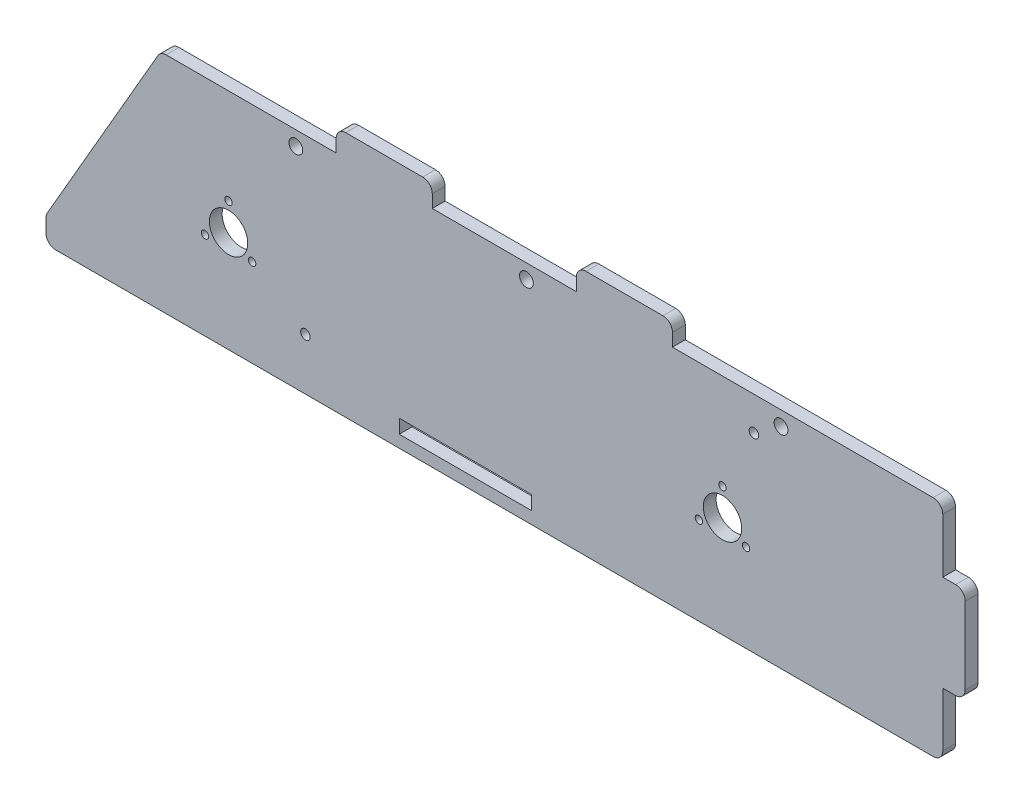
SolidWorks part; units mm, degrees
ref_plane "Front Plane" through (0, 0, 0) normal (0, 0, 1) x (1, 0, 0)
ref_plane "Top Plane" through (0, 0, 0) normal (0, 1, 0) x (1, 0, 0)
ref_plane "Right Plane" through (0, 0, 0) normal (1, 0, 0) x (0, 0, -1)
sketch "Sketch1" plane through (0, 0, 0) normal (0, 0, 1) x (1, 0, 0)
  line L0 (-128.1718, -30) -> (151.8282, -30)
  line L1 (-128.1718, -30) -> (-128.1718, -22)
  line L2 (-128.1718, -22) -> (-92.376, 40)
  line L5 (-37.566, 40) -> (-37.566, 47)
  line L6 (-37.566, 47) -> (-7.566, 47)
  line L7 (-7.566, 47) -> (-7.566, 40)
  line L8 (37.434, 40) -> (37.434, 47)
  line L9 (37.434, 47) -> (67.434, 47)
  line L10 (67.434, 47) -> (67.434, 40)
  line L11 (-92.376, 40) -> (-37.566, 40)
  line L12 (-7.566, 40) -> (37.434, 40)
  line L13 (67.434, 40) -> (151.8282, 40)
  line L16 (158.8282, 5) -> (158.8282, 20)
  line L17 (158.8282, 5) -> (158.8282, -10)
  line L18 (158.8282, -10) -> (151.8282, -10)
  line L19 (158.8282, 20) -> (151.8282, 20)
  line L20 (151.8282, 40) -> (151.8282, 20)
  line L21 (151.8282, -10) -> (151.8282, -30)
  line L22 (-17.8718, -21.85) -> (23.4282, -21.85)
  line L23 (-17.8718, -21.85) -> (-17.8718, -26.2)
  line L24 (-17.8718, -26.2) -> (23.4282, -26.2)
  line L25 (23.4282, -21.85) -> (23.4282, -26.2)
  circle A0 centre (-71.1757, 1.72) radius 6
  circle A3 centre (-71.1757, 1.72) radius 8.5 construction
  circle A4 centre (-71.1757, 10.22) radius 1.15
  circle A5 centre (-63.8145, -2.53) radius 1.15
  circle A6 centre (-78.537, -2.53) radius 1.15
  circle A7 centre (83.0482, 1.72) radius 6
  circle A8 centre (83.0482, 1.72) radius 8.5 construction
  circle A9 centre (83.0482, 10.22) radius 1.15
  circle A10 centre (90.4095, -2.53) radius 1.15
  circle A11 centre (75.687, -2.53) radius 1.15
  circle A12 centre (92.8604, 29.5) radius 1.5
  circle A13 centre (-50.1718, 35.5) radius 2.15
  circle A14 centre (21.8282, 35.5) radius 2.15
  circle A15 centre (101.3282, 35.5) radius 2.15
  circle A16 centre (-47.1718, -13.85) radius 1.5
  point P39 (151.8282, 30)
  dimension "D22" = 12
  dimension "D23" = 31.72
  dimension "D24" = 37.5
  dimension "D25" = 2.3
  dimension "D26" = 17
  dimension "D28" = 12
  dimension "D29" = 17
  dimension "D30" = 75.78
  dimension "D31" = 31.72
  dimension "D32" = 2.3
  dimension "D34" = 3
  dimension "D35" = 10.5
  dimension "D36" = 58.97
  dimension "D39" = 4.3
  dimension "D40" = 4.5
  dimension "D41" = 130
  dimension "D42" = 4.5
  dimension "D43" = 202
  dimension "D44" = 4.3
  dimension "D45" = 4.3
  dimension "D46" = 4.5
  dimension "D47" = 50.5
  dimension "D48" = 3
  dimension "D49" = 16.15
  dimension "D1" = 280
  dimension "D2" = 8
  dimension "D3" = 70
  dimension "D4" = 60
  dimension "D5" = 30
  dimension "D6" = 7
  dimension "D7" = 30
  dimension "D8" = 54.81
  dimension "D9" = 45
  dimension "D10" = 70
  dimension "D11" = 15
  dimension "D12" = 15
  dimension "D13" = 7
  dimension "D14" = 30
  dimension "D15" = 100
  dimension "D16" = 40
  dimension "D17" = 47
  dimension "D18" = 151.8282
  dimension "D19" = 20
  dimension "D20" = 41.3
  dimension "D21" = 4.35
  dimension "D37" = 3.8
  dimension "D38" = 110.3
  dimension "D50" = 199
  dimension "D27" = 3
  dimension "D33" = 3
extrude "Boss-Extrude1" add sketch "Sketch1" along normal blind 4
fillet "Fillet1" radius 3 11 edges at (-128.1718, -30, 2) (-128.1718, -22, 2) (-92.376, 40, 2) (-37.566, 47, 2) (-7.566, 47, 2) (37.434, 47, 2) (67.434, 47, 2) (151.8282, -30, 2) (158.8282, -10, 2) (158.8282, 20, 2) (151.8282, 40, 2)
